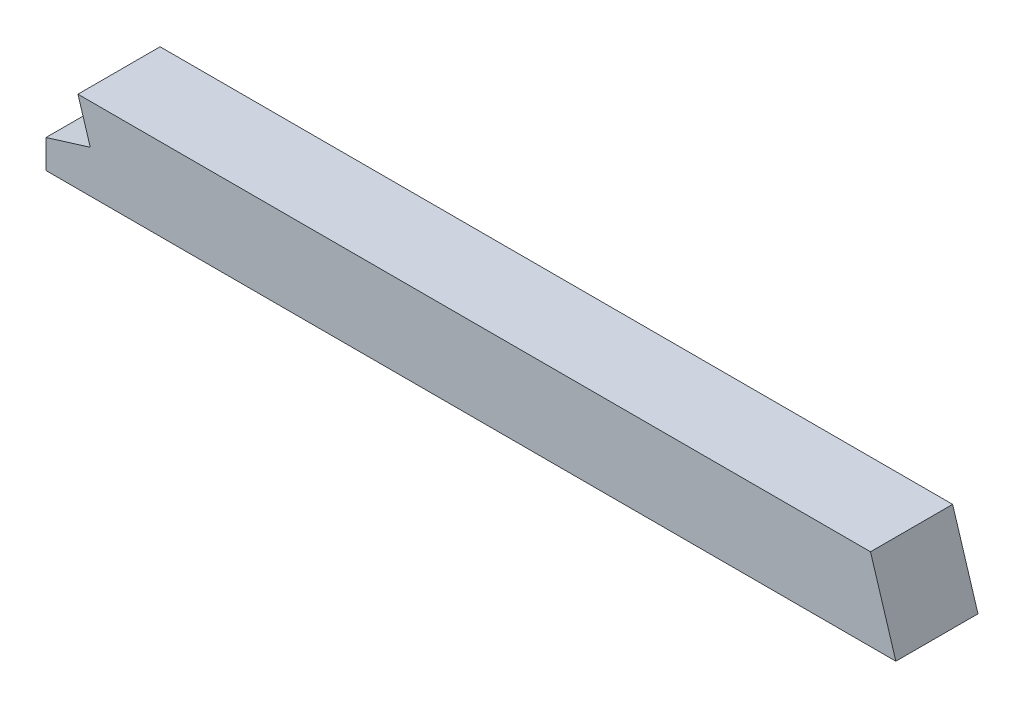
SolidWorks part; units mm, degrees
material "Pine"
ref_plane "X-Y Datum" through (0, 0, 0) normal (0, 0, 1) x (1, 0, 0)
ref_plane "X-Z Datum" through (0, 0, 0) normal (0, 1, 0) x (1, 0, 0)
ref_plane "Y-Z Datum" through (0, 0, 0) normal (1, 0, 0) x (0, 0, -1)
sketch "Sketch1" plane through (0, 0, 0) normal (1, 0, 0) x (0, 0, -1)
  line L1 (-19.05, 19.05) -> (19.05, 19.05)
  line L2 (-19.05, 19.05) -> (-19.05, -19.05)
  line L3 (-19.05, -19.05) -> (19.05, -19.05)
  line L4 (19.05, 19.05) -> (19.05, -19.05)
  line L5 (-19.05, 19.05) -> (19.05, -19.05) construction
  line L6 (-19.05, -19.05) -> (19.05, 19.05) construction
  point P0 (0, 0)
  dimension "D1" = 38.1
extrude "Boss-Extrude1" add sketch "Sketch1" along normal blind 394.2334
sketch "Sketch2" plane through (0, 0, 19.05) normal (0, 0, 1) x (1, 0, 0)
  line L0 (394.2334, -19.05) -> (382.4686, 19.05)
  line L1 (394.2334, 19.05) -> (0, 19.05) construction
  line L5 (394.2334, 19.05) -> (394.2334, -19.05) construction
  line L6 (382.4686, 19.05) -> (394.2334, 19.05)
  line L7 (394.2334, 19.05) -> (394.2334, -19.05)
  dimension "D1" = 17.16
extrude "Cut-Extrude1" cut sketch "Sketch2" against normal through all
sketch "Sketch3" plane through (0, 0, 19.05) normal (0, 0, 1) x (1, 0, 0)
  line L6 (-3.747, -6.9153) -> (20.5223, 0.5787)
  line L7 (20.5223, 0.5787) -> (5.5342, 49.1173)
  line L8 (5.5342, 49.1173) -> (-18.7351, 41.6233)
  line L9 (-18.7351, 41.6233) -> (-3.747, -6.9153)
  line L10 (394.2334, -19.05) -> (0, -19.05) construction
  point P2 (0, 0)
  point P3 (-1.3006, -13.1521)
  dimension "D1" = 17.16
  dimension "D2" = 25.4
  dimension "D3" = 50.8
  dimension "D4" = 12.7
extrude "Cut-Extrude2" cut sketch "Sketch3" against normal through all both
